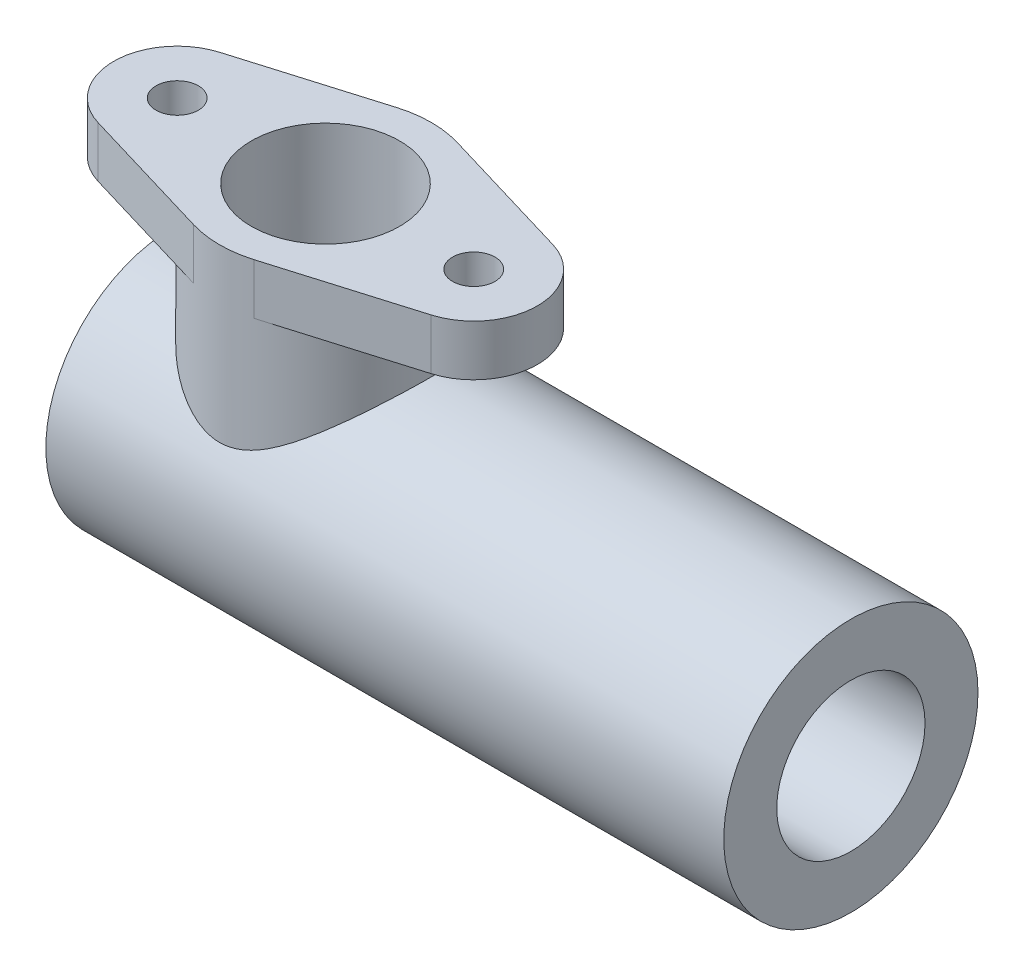
SolidWorks part; units mm, degrees
ref_plane "前视基准面" through (0, 0, 0) normal (0, 0, 1) x (1, 0, 0)
ref_plane "上视基准面" through (0, 0, 0) normal (0, 1, 0) x (1, 0, 0)
ref_plane "右视基准面" through (0, 0, 0) normal (1, 0, 0) x (0, 0, -1)
other "Configuration Table"
sketch "草图1" plane through (0, 0, 0) normal (0, 1, 0) x (1, 0, 0)
  line L0 (0, 82.8503) -> (0, -56.4263) construction
  line L1 (-94.1356, 0) -> (98.7231, 0) construction
  line L2 (-7.1429, 23.9579) -> (-39.2857, 14.3747)
  line L3 (-7.1429, -23.9579) -> (-39.2857, -14.3747)
  line L4 (7.1429, -23.9579) -> (39.2857, -14.3747)
  line L5 (7.1429, 23.9579) -> (39.2857, 14.3747)
  circle A0 centre (0, 0) radius 17.5
  arc A1 (-7.1429, -23.9579) -> (7.1429, -23.9579) centre (0, 0) ccw
  circle A2 centre (-35, 0) radius 5
  arc A3 (-39.2857, 14.3747) -> (-39.2857, -14.3747) centre (-35, 0) ccw
  circle A4 centre (35, 0) radius 5
  arc A5 (7.1429, -23.9579) -> (-7.1429, -23.9579) centre (0, 0) cw
  arc A6 (39.2857, 14.3747) -> (39.2857, -14.3747) centre (35, 0) cw
  arc A7 (-7.1429, 23.9579) -> (7.1429, 23.9579) centre (0, 0) cw
  arc A8 (7.1429, 23.9579) -> (-7.1429, 23.9579) centre (0, 0) ccw
  dimension "D1" = 35
  dimension "D2" = 50
  dimension "D3" = 10
  dimension "D5" = 30
  dimension "D4" = 70
extrude "凸台-拉伸1" add sketch "草图1" along normal blind 12 contours A7 L2 A3 L3 A1 L4 A6 L5 A0 A2 A4
sketch "草图3" plane through (0, 0, 0) normal (1, 0, 0) x (0, 0, -1)
  line L0 (0, 39.7635) -> (0, -62.4855) construction
  line L1 (14.3747, 12) -> (-14.3747, 12) construction
  circle A0 centre (0, -45) radius 17.5
  circle A1 centre (0, -45) radius 30
  dimension "D2" = 35
  dimension "D3" = 60
  dimension "D1" = 57
extrude "凸台-拉伸3" add sketch "草图3" along normal blind 124 and the other way blind 36 separate body
sketch "草图2" plane through (0, 0, 0) normal (0, -1, 0) x (1, 0, 0)
  circle A0 centre (0, 0) radius 25
  circle A1 centre (0, 0) radius 17.5 construction
  circle A2 centre (0, 0) radius 17.5
  dimension "D1" = 50
extrude "凸台-拉伸2" add sketch "草图2" along normal up to next
ref_plane "基准面1" through (44, 0, 0) normal (1, 0, 0) x (0, 0, -1)
sketch "草图4" plane through (44, 0, 0) normal (1, 0, 0) x (0, 0, -1)
  circle A0 centre (0, -45) radius 22
  dimension "D1" = 44
extrude "切除-拉伸1" cut sketch "草图4" against normal mid plane 100
sketch "草图5" plane through (0, 12, 0) normal (0, 1, 0) x (1, 0, 0)
  circle A0 centre (0, 0) radius 17.5 construction
  circle A1 centre (0, 0) radius 17.5
extrude "切除-拉伸8" cut sketch "草图5" against normal blind 57
